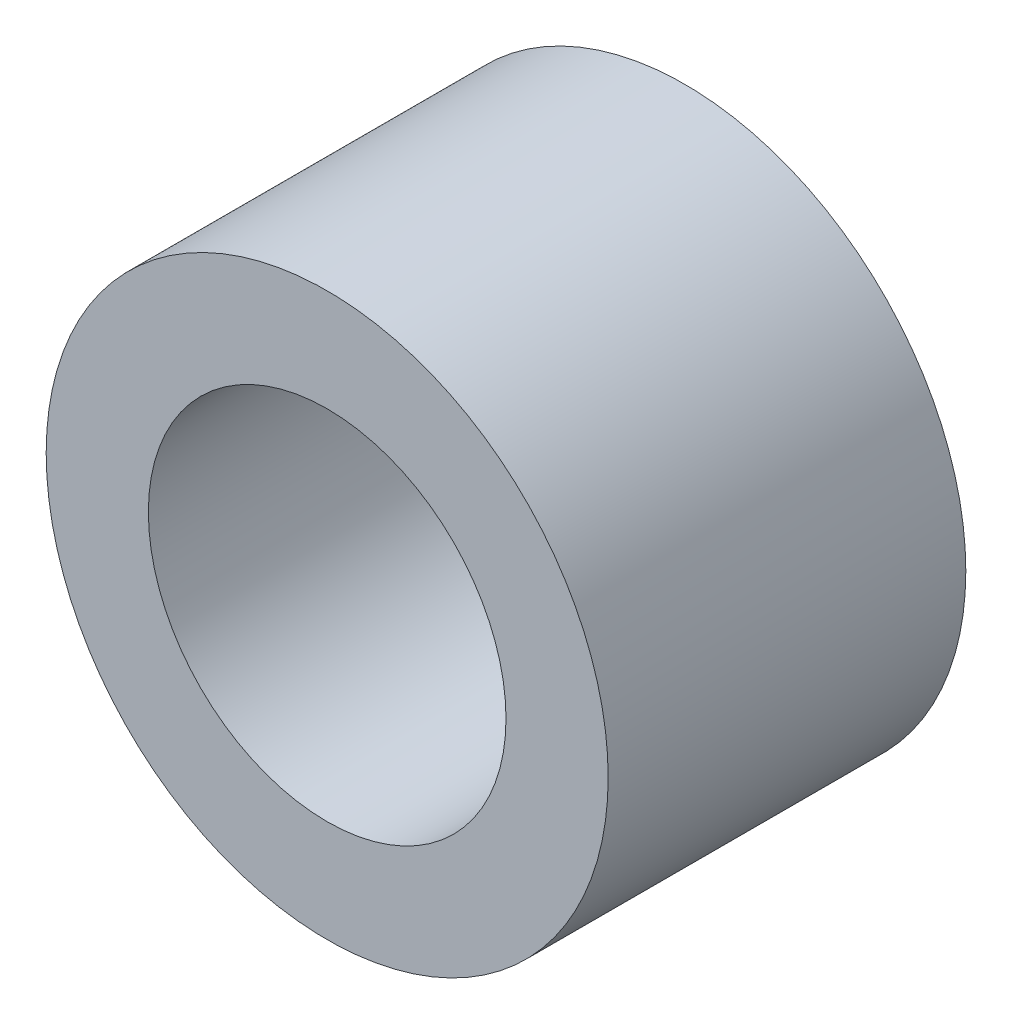
SolidWorks part; units mm, degrees
material "ABS"
ref_plane "前视基准面" through (0, 0, 0) normal (0, 0, 1) x (1, 0, 0)
ref_plane "上视基准面" through (0, 0, 0) normal (0, 1, 0) x (1, 0, 0)
ref_plane "右视基准面" through (0, 0, 0) normal (1, 0, 0) x (0, 0, -1)
sketch "草图1" plane through (0, 0, 0) normal (0, 0, 1) x (1, 0, 0)
  circle A0 centre (0, 0) radius 1.75
  circle A1 centre (0, 0) radius 2.75
  dimension "D1" = 3.5
  dimension "D2" = 5.5
extrude "凸台-拉伸1" add sketch "草图1" along normal blind 3.5
